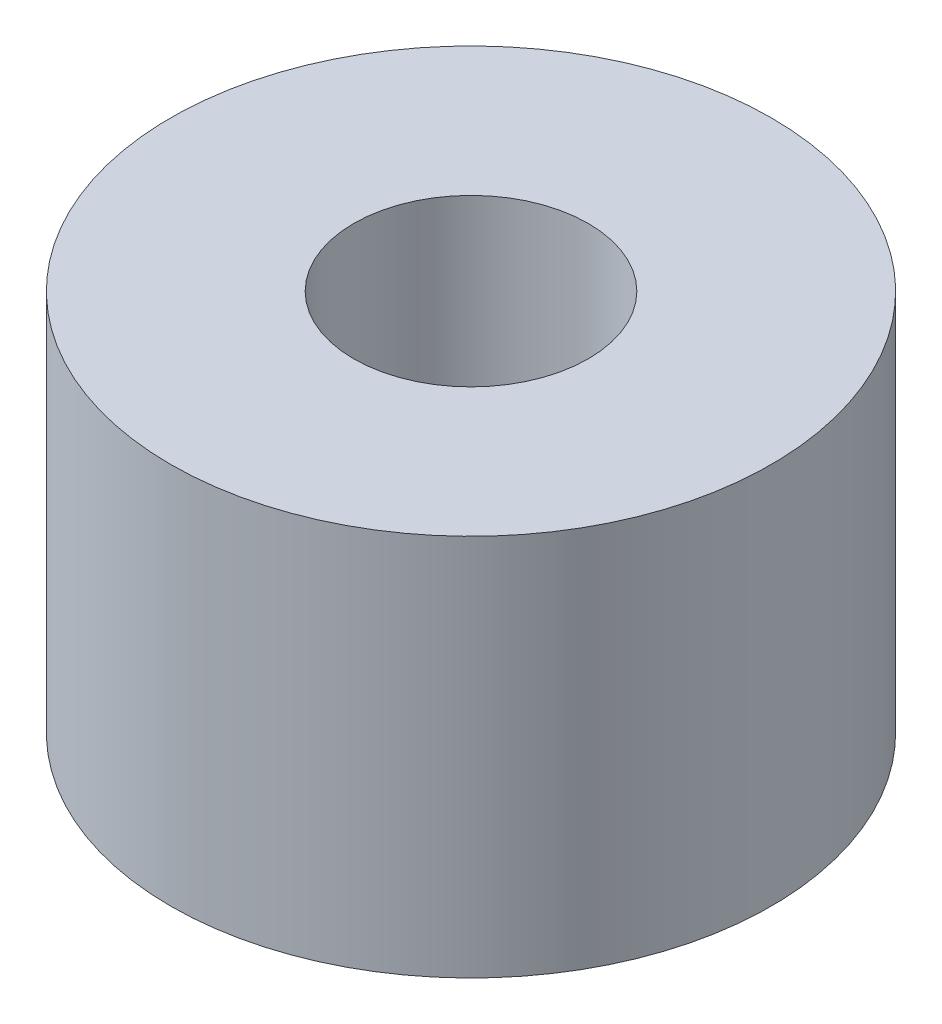
SolidWorks part; units mm, degrees
ref_plane "Front Plane" through (0, 0, 0) normal (0, 0, 1) x (1, 0, 0)
ref_plane "Top Plane" through (0, 0, 0) normal (0, 1, 0) x (1, 0, 0)
ref_plane "Right Plane" through (0, 0, 0) normal (1, 0, 0) x (0, 0, -1)
other "Configuration Table"
sketch "Sketch1" plane through (0, 0, 0) normal (0, 1, 0) x (1, 0, 0)
  circle A0 centre (0, 0) radius 12.7
  dimension "D1" = 25.4
extrude "Boss-Extrude1" add sketch "Sketch1" along normal blind 16.1798
sketch "Sketch4" plane through (0, 16.1798, 0) normal (0, 1, 0) x (1, 0, 0)
  point P0 (0, 0)
hole_wizard "7/16-20 Tapped Hole1" positions "Sketch4" profile "Sketch5" tap size "7/16-20" standard "ANSI Inch"
sketch "Sketch5" plane through (0, 16.1798, 0) normal (1, 0, 0) x (0, 0, 1)
  line L0 (0, 0) -> (0, 13.0048)
  line L1 (0, 13.0048) -> (4.9606, 10.0242)
  line L2 (4.9606, 10.0242) -> (4.9606, 0)
  line L5 (4.9606, 0) -> (0, 0)
  line L10 (0, 13.0048) -> (-4.9606, 10.0242) construction
  line L11 (0, -6.35) -> (0, 107.95) construction
  dimension "Tap Drill Dia." = 9.9212
  dimension "Tap Drill Depth" = 13.0048
  dimension "Drill Angle" = 118
equation "\"tip comp\"= 0.12in"
equation "\"wall thickness\"= 01 / 8in"
equation "\"depth\" = 0.392in"
equation "\"D1@Boss-Extrude1\"=\"tip comp\"+\"wall thickness\"+\"depth\""
